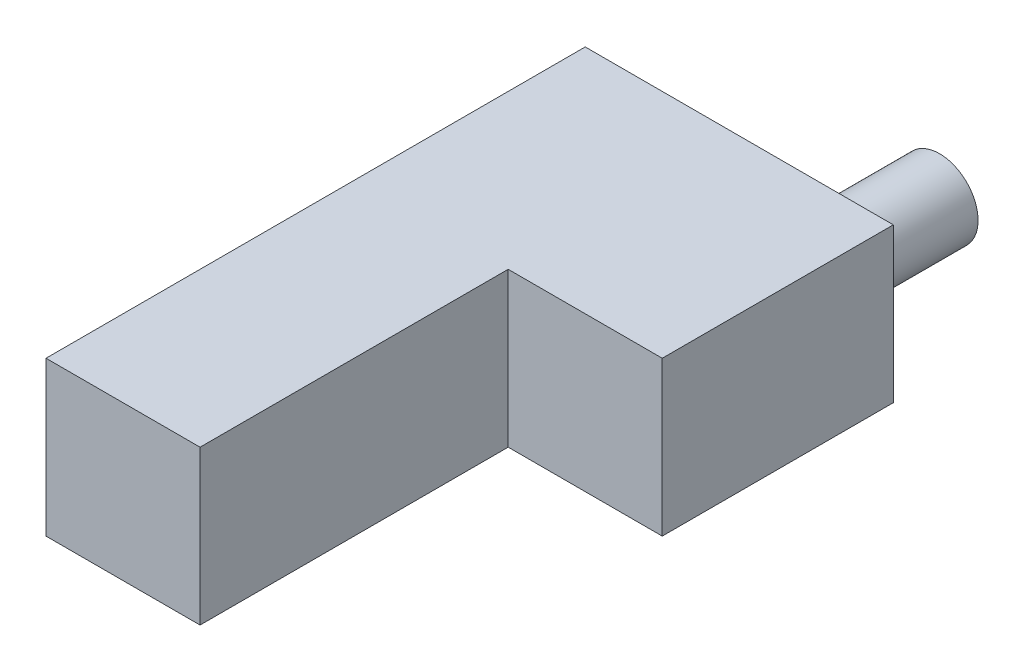
SolidWorks part; units mm, degrees
ref_plane "Front Plane" through (0, 0, 0) normal (0, 0, 1) x (1, 0, 0)
ref_plane "Top Plane" through (0, 0, 0) normal (0, 1, 0) x (1, 0, 0)
ref_plane "Right Plane" through (0, 0, 0) normal (1, 0, 0) x (0, 0, -1)
sketch "Sketch1" plane through (0, 0, 0) normal (0, 1, 0) x (1, 0, 0)
  line L1 (-5, -17.5) -> (5, -17.5)
  line L2 (-5, -17.5) -> (-5, 17.5)
  line L3 (-5, 17.5) -> (5, 17.5)
  line L4 (5, -17.5) -> (5, 2.5)
  line L7 (-5, 17.5) -> (5, 17.5)
  line L11 (5, 17.5) -> (15, 17.5)
  line L13 (5, 2.5) -> (15, 2.5)
  line L14 (15, 17.5) -> (15, 2.5)
  point P0 (0, 0)
extrude "Boss-Extrude1" add sketch "Sketch1" along normal blind 10 contours L3 L11 L14 L13 L4 L1 L2
sketch "Sketch2" plane through (0, 0, -17.5) normal (0, 0, -1) x (-1, 0, 0)
  line L0 (-15, 5) -> (-10, 5) construction
  line L1 (-15, 10) -> (-15, 0) construction
  line L2 (-10, 10) -> (-10, 5) construction
  line L4 (5, 10) -> (-15, 10) construction
  circle A0 centre (-10, 5) radius 2.5
extrude "Boss-Extrude2" add sketch "Sketch2" along normal blind 8
